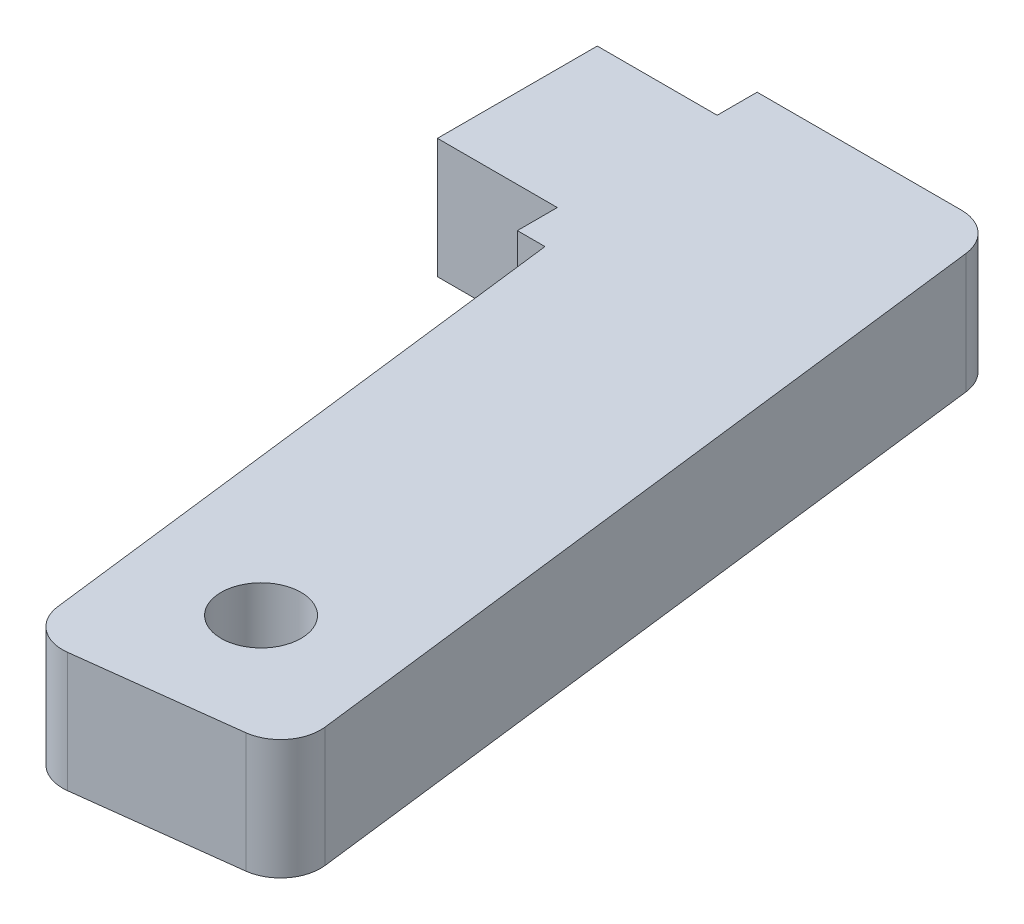
SolidWorks part; units mm, degrees
ref_plane "Front Plane" through (0, 0, 0) normal (0, 0, 1) x (1, 0, 0)
ref_plane "Top Plane" through (0, 0, 0) normal (0, 1, 0) x (1, 0, 0)
ref_plane "Right Plane" through (0, 0, 0) normal (1, 0, 0) x (0, 0, -1)
sketch "Sketch2" plane through (0, 0, 0) normal (0, 1, 0) x (1, 0, 0)
  line L3 (20.7482, 19.9333) -> (14.7482, 19.9333)
  line L4 (14.7482, 13.9333) -> (15.4399, 13.9333)
  line L5 (15.4399, 13.9333) -> (17.2679, -0.9549)
  line L6 (17.2679, -0.9549) -> (23.2232, -0.2236)
  line L7 (23.2232, -0.2236) -> (20.7482, 19.9333)
  line L8 (14.7482, 18.9333) -> (11.7482, 18.9333)
  line L9 (11.7482, 18.9333) -> (11.7482, 14.9333)
  line L10 (11.7482, 14.9333) -> (14.7482, 14.9333)
  line L12 (14.7482, 19.9333) -> (14.7482, 18.9333)
  line L13 (14.7482, 14.9333) -> (14.7482, 13.9333)
  line L14 (11.7482, 16.9333) -> (21.1868, 16.3618) construction
  line L15 (20.2456, -0.5892) -> (18.1416, 16.5462) construction
  circle A1 centre (19.88, 2.3884) radius 1
  dimension "D7" = 2
  dimension "D8" = 3
  dimension "D1" = 97
  dimension "D2" = 15
  dimension "D3" = 6
  dimension "D4" = 6
  dimension "D5" = 6
extrude "Boss-Extrude1" add sketch "Sketch2" along normal blind 3
fillet "Fillet1" radius 1 3 edges at (17.2679, 1.5, 0.9549) (23.2232, 1.5, 0.2236) (20.7482, 1.5, -19.9333)
